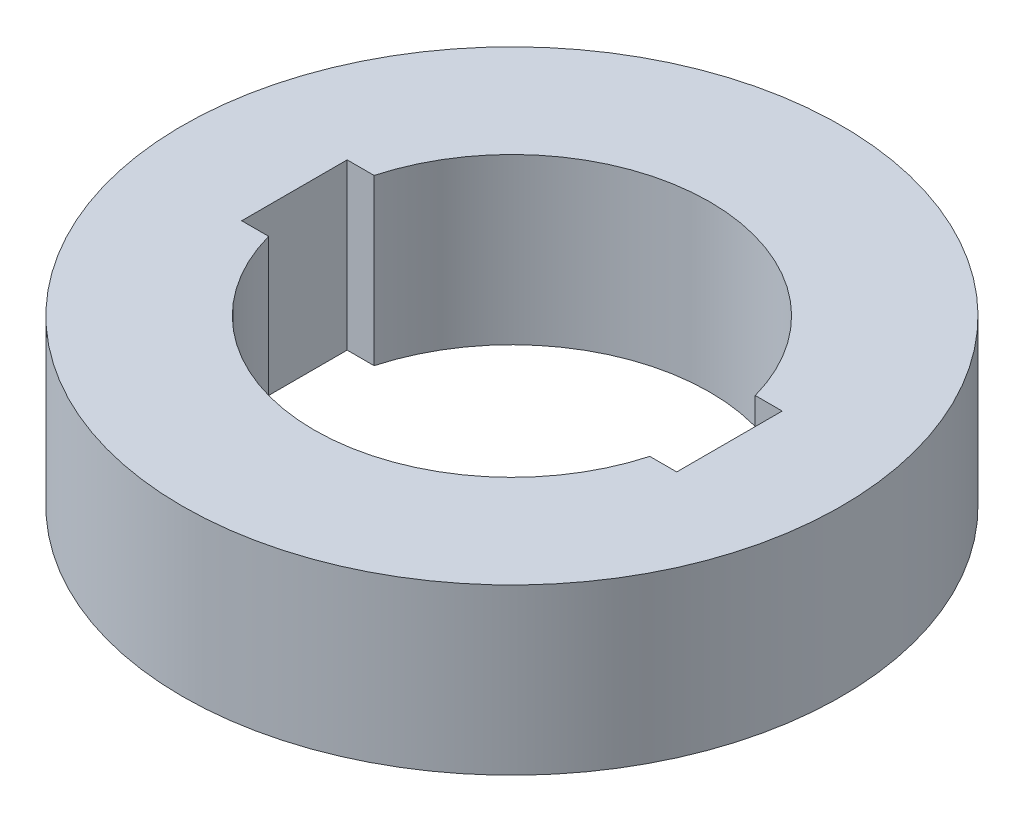
SolidWorks part; units mm, degrees
ref_plane "Front Plane" through (0, 0, 0) normal (0, 0, 1) x (1, 0, 0)
ref_plane "Top Plane" through (0, 0, 0) normal (0, 1, 0) x (1, 0, 0)
ref_plane "Right Plane" through (0, 0, 0) normal (1, 0, 0) x (0, 0, -1)
sketch "Sketch2" plane through (0, 0, 0) normal (0, 1, 0) x (1, 0, 0)
  circle A0 centre (0, 0) radius 50
  dimension "D1" = 100
extrude "Boss-Extrude1" add sketch "Sketch2" along normal blind 25
sketch "Sketch3" plane through (0, 25, 0) normal (0, 1, 0) x (1, 0, 0)
  line L0 (0, 0) -> (33, 0) construction
  line L1 (33, 8) -> (33, -8)
  line L2 (33, 8) -> (28.9137, 8)
  line L3 (33, -8) -> (28.9137, -8)
  line L4 (0, -30) -> (0, 30) construction
  line L5 (-33, -8) -> (-28.9137, -8)
  line L6 (-33, 8) -> (-33, -8)
  line L7 (-33, 8) -> (-28.9137, 8)
  arc A0 (28.9137, 8) -> (-28.9137, 8) centre (0, 0) ccw
  arc A1 (-28.9137, -8) -> (28.9137, -8) centre (0, 0) ccw
  point P8 (33, 0)
  point P10 (0, 0)
  point P11 (0, 0)
  point P12 (0, -30)
  point P13 (0, 0)
  dimension "D1" = 60
  dimension "D2" = 33
  dimension "D3" = 16
extrude "Cut-Extrude1" cut sketch "Sketch3" against normal blind 25
